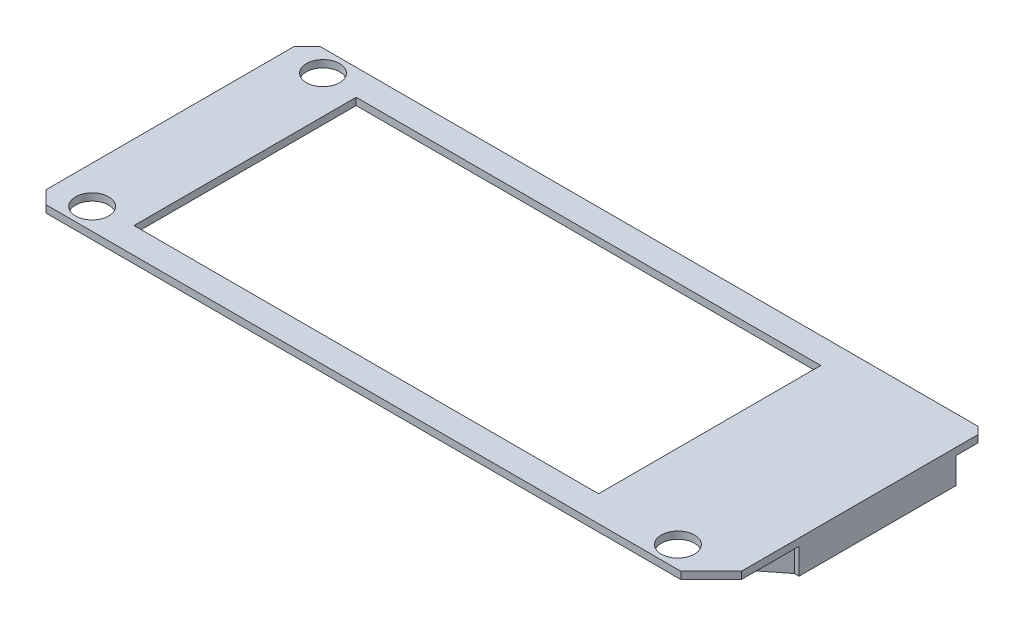
SolidWorks part; units mm, degrees
ref_plane "Спереди" through (0, 0, 0) normal (0, 0, 1) x (1, 0, 0)
ref_plane "Сверху" through (0, 0, 0) normal (0, 1, 0) x (1, 0, 0)
ref_plane "Справа" through (0, 0, 0) normal (1, 0, 0) x (0, 0, -1)
other "Configuration Table"
sketch "Эскиз1" plane through (0, 0, 0) normal (0, 1, 0) x (1, 0, 0)
  line L26 (22.8159, 9.8398) -> (-22.7841, 9.8398)
  line L27 (-22.7841, 9.8398) -> (-23.6841, 8.9398)
  line L28 (-23.6841, 8.9398) -> (-23.6841, -8.2602)
  line L29 (-23.6841, -8.2602) -> (-22.7841, -9.1602)
  line L30 (-22.7841, -9.1602) -> (21.2159, -9.1602)
  line L31 (21.2159, -9.1602) -> (23.3159, -7.0602)
  line L32 (23.3159, -7.0602) -> (23.3159, -3.2602)
  line L33 (23.3159, -3.2602) -> (23.029, -3.2602)
  line L34 (21.1888, -4.6602) -> (21.1888, -5.6602)
  line L35 (21.1888, -5.6602) -> (19.8888, -5.6602)
  line L36 (19.8888, -5.6602) -> (19.8888, -4.6602)
  line L37 (19.8888, -4.6602) -> (17.3159, -4.6602)
  line L38 (17.3159, -4.6602) -> (17.3159, -8.3602)
  line L39 (17.3159, -8.3602) -> (-18.8841, -8.3602)
  line L40 (-18.8841, -8.3602) -> (-18.8841, -6.6602)
  line L41 (-18.8841, -6.6602) -> (-19.6841, -5.8602)
  line L42 (-19.6841, -5.8602) -> (-19.6841, 6.5398)
  line L43 (-19.6841, 6.5398) -> (-18.8841, 7.3398)
  line L44 (-18.8841, 7.3398) -> (-18.8841, 9.0398)
  line L45 (-18.8841, 9.0398) -> (17.3159, 9.0398)
  line L46 (17.3159, 9.0398) -> (17.3159, 8.5398)
  line L47 (19.3159, 8.2084) -> (19.3159, 9.1398)
  line L48 (19.3159, 9.1398) -> (21.5301, 9.1398)
  line L49 (23.029, 7.9398) -> (23.3159, 7.9398)
  line L50 (23.3159, 7.9398) -> (23.3159, 9.3398)
  line L51 (23.3159, 9.3398) -> (22.8159, 9.8398)
  arc A3 (21.1888, -4.6602) -> (23.029, -3.2602) centre (17.3159, 2.3398) ccw
  arc A4 (19.3159, 8.2084) -> (17.3159, 8.5398) centre (17.3159, 2.3398) ccw
  arc A5 (23.029, 7.9398) -> (21.5301, 9.1398) centre (17.3159, 2.3398) ccw
  arc A6 (18.5659, -7.6602) -> (20.4659, -7.6602) centre (19.5159, -7.6602) ccw
  arc A7 (20.4659, -7.6602) -> (18.5659, -7.6602) centre (19.5159, -7.6602) ccw
  arc A8 (-22.0341, -7.6602) -> (-20.1341, -7.6602) centre (-21.0841, -7.6602) ccw
  arc A9 (-20.1341, -7.6602) -> (-22.0341, -7.6602) centre (-21.0841, -7.6602) ccw
  arc A10 (-22.0341, 8.3398) -> (-20.1341, 8.3398) centre (-21.0841, 8.3398) ccw
  arc A11 (-20.1341, 8.3398) -> (-22.0341, 8.3398) centre (-21.0841, 8.3398) ccw
extrude "Бобышка-Вытянуть1" add sketch "Эскиз1" along normal blind 0.5
sketch "Эскиз2" plane through (0, 0, 0) normal (0, -1, 0) x (-1, 0, 0)
  line L0 (-17.3159, -4.6602) -> (-17.3159, 9.8398)
  line L1 (-22.8159, 9.8398) -> (22.7841, 9.8398) construction
  line L2 (-17.3159, 9.8398) -> (-22.8159, 9.8398)
  line L3 (-22.8159, 9.8398) -> (-23.3159, 9.3398)
  line L4 (-23.3159, 9.3398) -> (-23.3159, -7.0602)
  line L5 (-23.3159, -7.0602) -> (-21.1888, -5.6602)
  line L6 (-21.1888, -5.6602) -> (-17.3159, -5.6602)
  line L7 (-17.3159, -4.6602) -> (-17.3159, -8.3602) construction
  line L8 (-17.3159, -5.6602) -> (-17.3159, -4.6602)
extrude "Бобышка-Вытянуть2" add sketch "Эскиз2" against normal blind 0.5
sketch "Эскиз3" plane through (0, 0, 0) normal (0, -1, 0) x (-1, 0, 0)
  line L0 (18.8841, 9.0398) -> (-17.3159, 9.0398) construction
  line L1 (-17.3159, -8.3602) -> (-13.7159, -8.3602)
  line L2 (-17.3159, -8.3602) -> (-17.3159, 9.0398)
  line L3 (-17.3159, 9.0398) -> (-13.7159, 9.0398)
  line L4 (-13.7159, -8.3602) -> (-13.7159, 9.0398)
  line L5 (18.8841, -8.3602) -> (18.8841, -6.6602) construction
  line L6 (-13.7159, -8.3602) -> (18.8841, -8.3602)
  line L7 (-13.7159, -8.3602) -> (-13.7159, -7.3602)
  line L8 (-13.7159, -7.3602) -> (18.8841, -7.3602)
  line L9 (18.8841, -8.3602) -> (18.8841, -7.3602)
  line L10 (18.8841, 7.3398) -> (18.8841, 9.0398) construction
  line L11 (-13.7159, 9.0398) -> (18.8841, 9.0398)
  line L12 (-13.7159, 9.0398) -> (-13.7159, 8.0398)
  line L13 (-13.7159, 8.0398) -> (18.8841, 8.0398)
  line L14 (18.8841, 9.0398) -> (18.8841, 8.0398)
  line L16 (18.4841, 8.0398) -> (19.728, 8.0398)
  line L17 (18.4841, 8.0398) -> (18.4841, -7.7602)
  line L18 (18.4841, -7.7602) -> (19.728, -7.7602)
  line L19 (19.728, 8.0398) -> (19.728, -7.7602)
  line M13 (-17.3159, -8.3602) -> (-17.3159, 9.0398)
  line M14 (-17.3159, 9.0398) -> (18.8841, 9.0398)
  line M15 (18.8841, 9.0398) -> (18.8841, 7.3398)
  line M19 (18.8841, -6.6602) -> (18.8841, -8.3602)
  line M20 (18.8841, -8.3602) -> (-17.3159, -8.3602)
  dimension "D1" = 3.6
  dimension "D2" = 1
  dimension "D3" = 1
  dimension "D4" = 0.4
extrude "Бобышка-Вытянуть3" add sketch "Эскиз3" against normal blind 0.5 contours L8 L4 M20 M19 | L4 L13 M15 M14 | L4 M20 M14 M13 | L17 L16 L19 L18
sketch "Эскиз6" plane through (0, 0, 0) normal (0, 1, 0) x (1, 0, 0)
  line L26 (22.8159, 9.8398) -> (-22.7841, 9.8398)
  line L27 (-22.7841, 9.8398) -> (-23.6841, 8.9398)
  line L28 (-23.6841, 8.9398) -> (-23.6841, -8.2602)
  line L29 (-23.6841, -8.2602) -> (-22.7841, -9.1602)
  line L30 (-22.7841, -9.1602) -> (21.2159, -9.1602)
  line L31 (21.2159, -9.1602) -> (23.3159, -7.0602)
  line L32 (23.3159, -7.0602) -> (23.3159, -3.2602)
  line L33 (23.3159, -3.2602) -> (23.029, -3.2602)
  line L34 (21.1888, -4.6602) -> (21.1888, -5.6602)
  line L35 (21.1888, -5.6602) -> (19.8888, -5.6602)
  line L36 (19.8888, -5.6602) -> (19.8888, -4.6602)
  line L37 (19.8888, -4.6602) -> (17.3159, -4.6602)
  line L38 (17.3159, -4.6602) -> (17.3159, -8.3602)
  line L39 (17.3159, -8.3602) -> (-18.8841, -8.3602)
  line L40 (-18.8841, -8.3602) -> (-18.8841, -6.6602)
  line L41 (-18.8841, -6.6602) -> (-19.6841, -5.8602)
  line L42 (-19.6841, -5.8602) -> (-19.6841, 6.5398)
  line L43 (-19.6841, 6.5398) -> (-18.8841, 7.3398)
  line L44 (-18.8841, 7.3398) -> (-18.8841, 9.0398)
  line L45 (-18.8841, 9.0398) -> (17.3159, 9.0398)
  line L46 (17.3159, 9.0398) -> (17.3159, 8.5398)
  line L47 (19.3159, 8.2084) -> (19.3159, 9.1398)
  line L48 (19.3159, 9.1398) -> (21.5301, 9.1398)
  line L49 (23.029, 7.9398) -> (23.3159, 7.9398)
  line L50 (23.3159, 7.9398) -> (23.3159, 9.3398)
  line L51 (23.3159, 9.3398) -> (22.8159, 9.8398)
  line L52 (23.3159, 7.8218) -> (23.3159, -3.0621)
  line L53 (23.3159, -7.0602) -> (23.3159, 9.3398) construction
  line L54 (23.3159, -3.0621) -> (22.9997, -3.0621)
  line L55 (22.9997, -3.0621) -> (21.2616, -4.4246)
  line L56 (21.2616, -4.4246) -> (21.0248, -4.4246)
  line L57 (21.0248, -4.4246) -> (21.0248, -5.4163)
  line L58 (21.0248, -5.4163) -> (20.0308, -5.4163)
  line L59 (20.0308, -5.4163) -> (20.0308, -4.4246)
  line L60 (20.0308, -4.4246) -> (19.718, -4.4246)
  line L61 (19.718, -4.4246) -> (19.718, 8.9933)
  line L62 (19.718, 8.9933) -> (21.5301, 8.9933)
  line L63 (21.5301, 8.9933) -> (22.9525, 7.8218)
  line L64 (22.9525, 7.8218) -> (23.3159, 7.8218)
  arc A3 (21.1888, -4.6602) -> (23.029, -3.2602) centre (17.3159, 2.3398) ccw
  arc A4 (19.3159, 8.2084) -> (17.3159, 8.5398) centre (17.3159, 2.3398) ccw
  arc A5 (23.029, 7.9398) -> (21.5301, 9.1398) centre (17.3159, 2.3398) ccw
  arc A6 (18.5659, -7.6602) -> (20.4659, -7.6602) centre (19.5159, -7.6602) ccw
  arc A7 (20.4659, -7.6602) -> (18.5659, -7.6602) centre (19.5159, -7.6602) ccw
  arc A8 (-22.0341, -7.6602) -> (-20.1341, -7.6602) centre (-21.0841, -7.6602) ccw
  arc A9 (-20.1341, -7.6602) -> (-22.0341, -7.6602) centre (-21.0841, -7.6602) ccw
  arc A10 (-22.0341, 8.3398) -> (-20.1341, 8.3398) centre (-21.0841, 8.3398) ccw
  arc A11 (-20.1341, 8.3398) -> (-22.0341, 8.3398) centre (-21.0841, 8.3398) ccw
extrude "Бобышка-Вытянуть4" add sketch "Эскиз6" against normal blind 1.8 contours L64 L52 L54 L55 L56 L57 L58 L59 L60 L61 L62 L63
sketch "Эскиз7" plane through (0, 0.5, 0) normal (0, 1, 0) x (1, 0, 0)
  circle A0 centre (-21.0841, 8.3398) radius 1.15
  circle A1 centre (-21.0841, -7.6602) radius 1.15
  circle A2 centre (19.5159, -7.6602) radius 1.15
  dimension "D1" = 2.3
  dimension "D2" = 2.3
  dimension "D3" = 2.3
extrude "Вырез-Вытянуть1" cut sketch "Эскиз7" against normal blind 10
